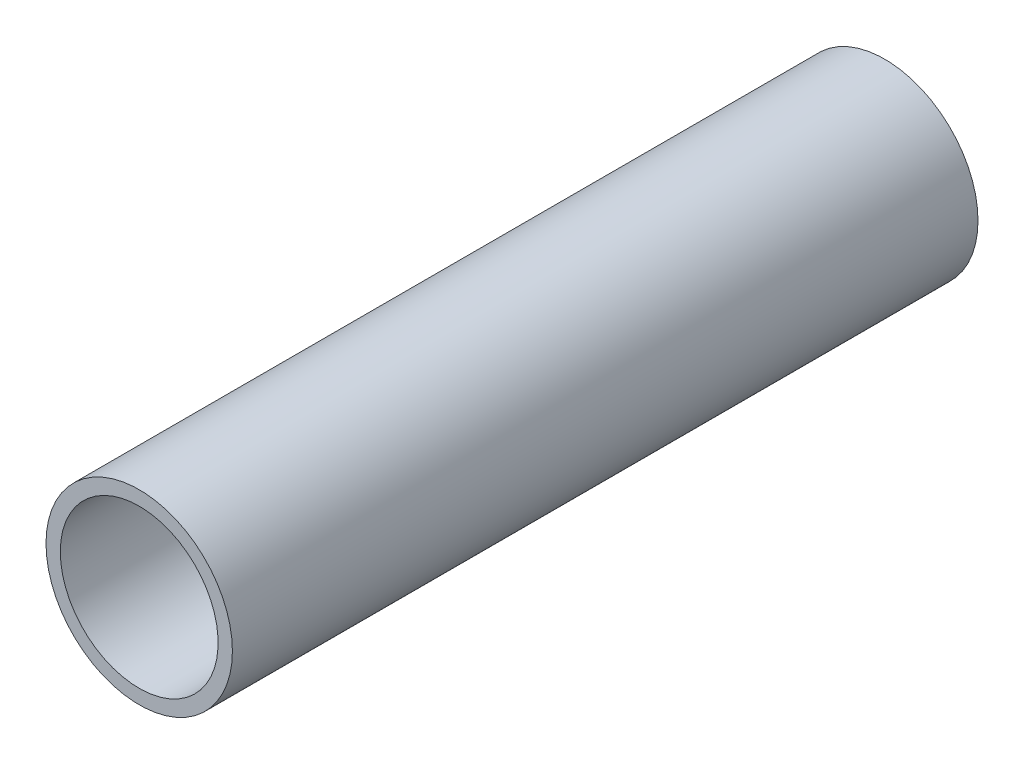
SolidWorks part; units mm, degrees
ref_plane "Front" through (0, 0, 0) normal (0, 0, 1) x (1, 0, 0)
ref_plane "Top" through (0, 0, 0) normal (0, 1, 0) x (1, 0, 0)
ref_plane "Right" through (0, 0, 0) normal (1, 0, 0) x (0, 0, -1)
sketch "Sketch1" plane through (0, 0, 0) normal (0, 0, 1) x (1, 0, 0)
  circle A0 centre (0, 0) radius 19.05
  circle A1 centre (0, 0) radius 16.129
  dimension "D1" = 38.1
  dimension "D2" = 32.258
extrude "Boss-Extrude1" add sketch "Sketch1" along normal blind 152.4
